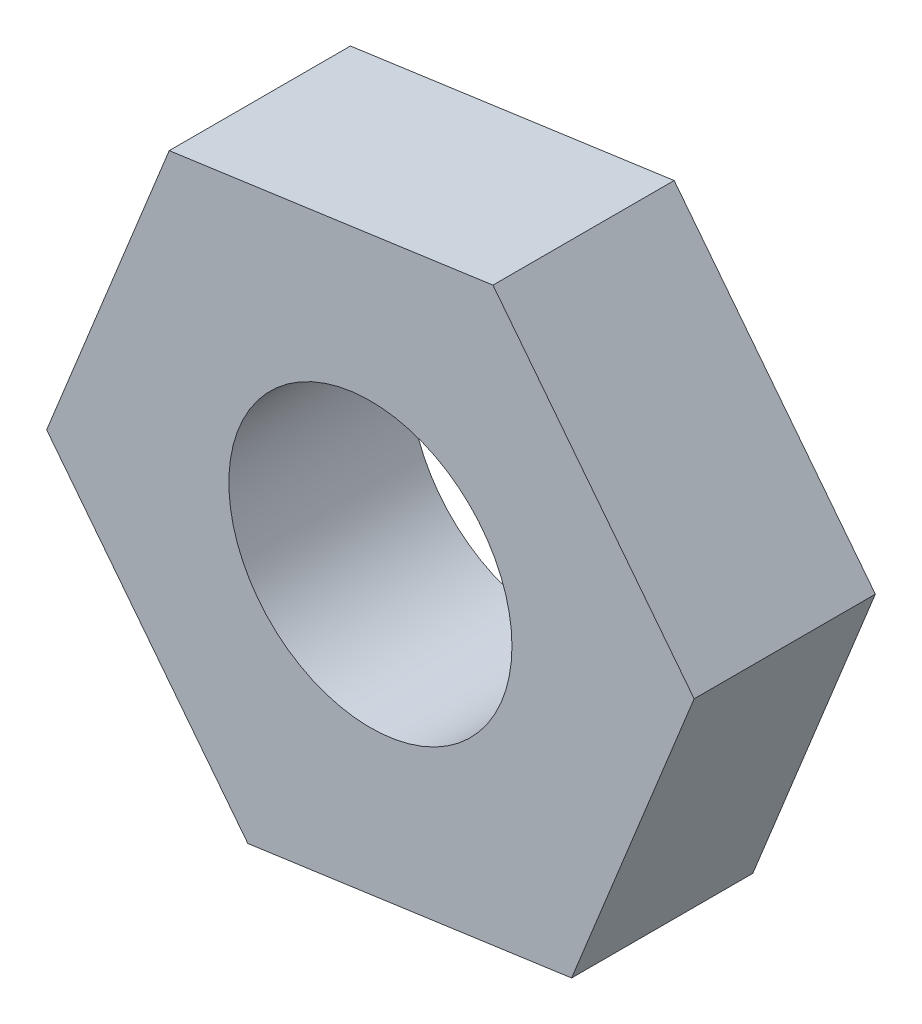
SolidWorks part; units mm, degrees
material "AISI 1020"
ref_plane "Alzado" through (0, 0, 0) normal (0, 0, 1) x (1, 0, 0)
ref_plane "Planta" through (0, 0, 0) normal (0, 1, 0) x (1, 0, 0)
ref_plane "Vista lateral" through (0, 0, 0) normal (1, 0, 0) x (0, 0, -1)
sketch "Croquis1" plane through (0, 0, 0) normal (0, 0, 1) x (1, 0, 0)
  line L1 (-3.6307, -0.509) -> (-1.3745, -3.3988)
  line L2 (-1.3745, -3.3988) -> (2.2562, -2.8897)
  line L3 (2.2562, -2.8897) -> (3.6307, 0.509)
  line L4 (3.6307, 0.509) -> (1.3745, 3.3988)
  line L5 (1.3745, 3.3988) -> (-2.2562, 2.8897)
  line L6 (-2.2562, 2.8897) -> (-3.6307, -0.509)
  circle A0 centre (0, 0) radius 3.175 construction
  circle A1 centre (0, 0) radius 1.5875
  dimension "D1" = 6.35
  dimension "D2" = 3.175
extrude "TUERCA" add sketch "Croquis1" along normal blind 2.032
